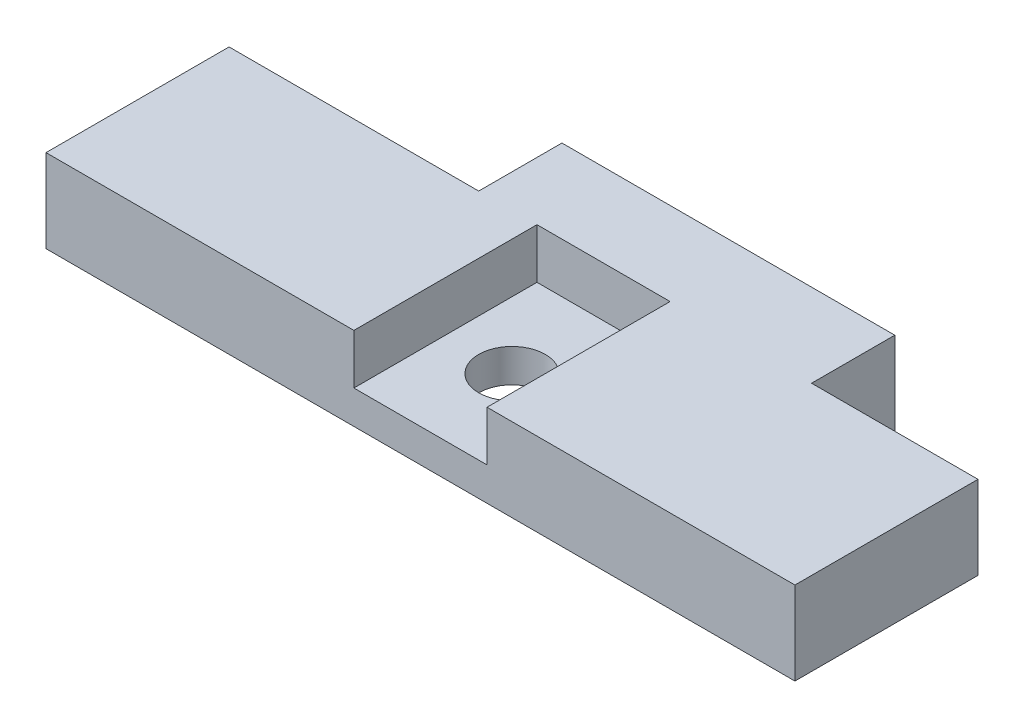
SolidWorks part; units mm, degrees
ref_plane "Plan de face" through (0, 0, 0) normal (0, 0, 1) x (1, 0, 0)
ref_plane "Plan de dessus" through (0, 0, 0) normal (0, 1, 0) x (1, 0, 0)
ref_plane "Plan de droite" through (0, 0, 0) normal (1, 0, 0) x (0, 0, -1)
sketch "Esquisse1" plane through (0, 0, 0) normal (0, 1, 0) x (1, 0, 0)
  line L0 (-7.5, 8) -> (-7.5, 3)
  line L1 (-7.5, 8) -> (12.5, 8)
  line L2 (-22.5, 3) -> (-22.5, -8)
  line L3 (-22.5, -8) -> (22.5, -8)
  line L4 (22.5, 3) -> (22.5, -8)
  line L5 (-22.5, 8) -> (22.5, -8) construction
  line L6 (-22.5, -8) -> (22.5, 8) construction
  line L7 (12.5, 8) -> (12.5, 3)
  line L8 (12.5, 3) -> (22.5, 3)
  line L9 (-7.5, 3) -> (-22.5, 3)
  point P0 (0, 0)
  point P12 (0, 0)
  dimension "D1" = 20
  dimension "D2" = 45
  dimension "D3" = 10
  dimension "D4" = 5
  dimension "D5" = 5
  dimension "D6" = 16
  dimension "D7" = 10
extrude "Boss.-Extru.3" add sketch "Esquisse1" along normal blind 5
sketch "Esquisse4" plane through (0, 5, 0) normal (0, 1, 0) x (1, 0, 0)
  line L0 (4, -8) -> (4, 3)
  line L1 (-22.5, -8) -> (22.5, -8) construction
  line L2 (0, -8) -> (0, 4.6796)
  line L3 (-4, -8) -> (-4, 3)
  line L4 (4, 3) -> (-4, 3)
  line L5 (4, -8) -> (-4, -8)
  dimension "D1" = 11
  dimension "D2" = 8
extrude "Enlèv. mat.-Extru.3" cut sketch "Esquisse4" against normal blind 3
sketch "Esquisse5" plane through (0, 5, 0) normal (0, 1, 0) x (1, 0, 0)
  line L0 (-4, -8) -> (4, -8) construction
  circle A0 centre (0, -2.5) radius 2
  dimension "D1" = 4
  dimension "D2" = 5.5
extrude "Enlèv. mat.-Extru.7" cut sketch "Esquisse5" against normal through all
